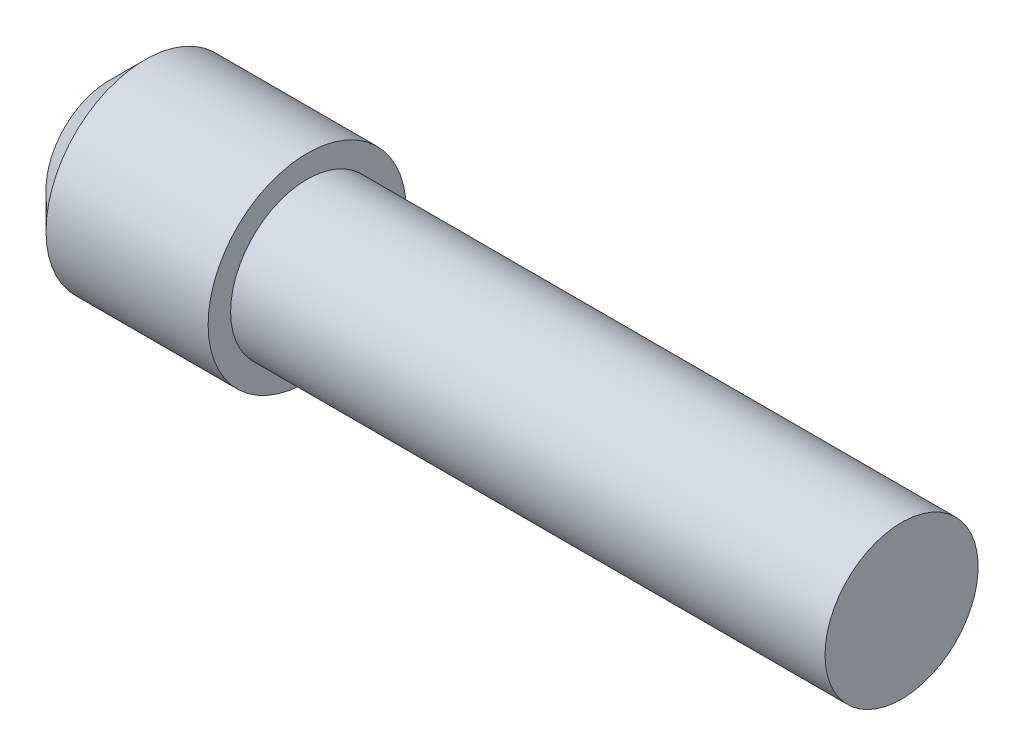
SolidWorks part; units mm, degrees
ref_plane "Front Plane" through (0, 0, 0) normal (0, 0, 1) x (1, 0, 0)
ref_plane "Top Plane" through (0, 0, 0) normal (0, 1, 0) x (1, 0, 0)
ref_plane "Right Plane" through (0, 0, 0) normal (1, 0, 0) x (0, 0, -1)
sketch "Sketch1" plane through (0, 0, 0) normal (0, 0, 1) x (1, 0, 0)
  line L0 (-9.4589, 0) -> (1.0894, 0) construction
  line L1 (0, 2.75) -> (-5.5, 2.75)
  line L2 (-5.5, 2.75) -> (-5.5, 0)
  line L3 (-5.5, 0) -> (16.5, 0)
  line L4 (0, 2.75) -> (0, 2.125)
  line L5 (0, 2.125) -> (0, 0) construction
  line L6 (0, 2.125) -> (16.5, 2.125)
  line L7 (16.5, 2.125) -> (16.5, 0)
  line L8 (9.5, 0) -> (9.5, 2.125) construction
  dimension "D1" = 9.5
  dimension "OD" = 5.5
  dimension "ID" = 4.25
  dimension "D2" = 7
  dimension "D3" = 5.5
revolve "Revolve1" add sketch "Sketch1" angle 360 about L0
chamfer "Chamfer1" distance 1 angle 45 1 edges at (-5.5, 0, 2.75)
